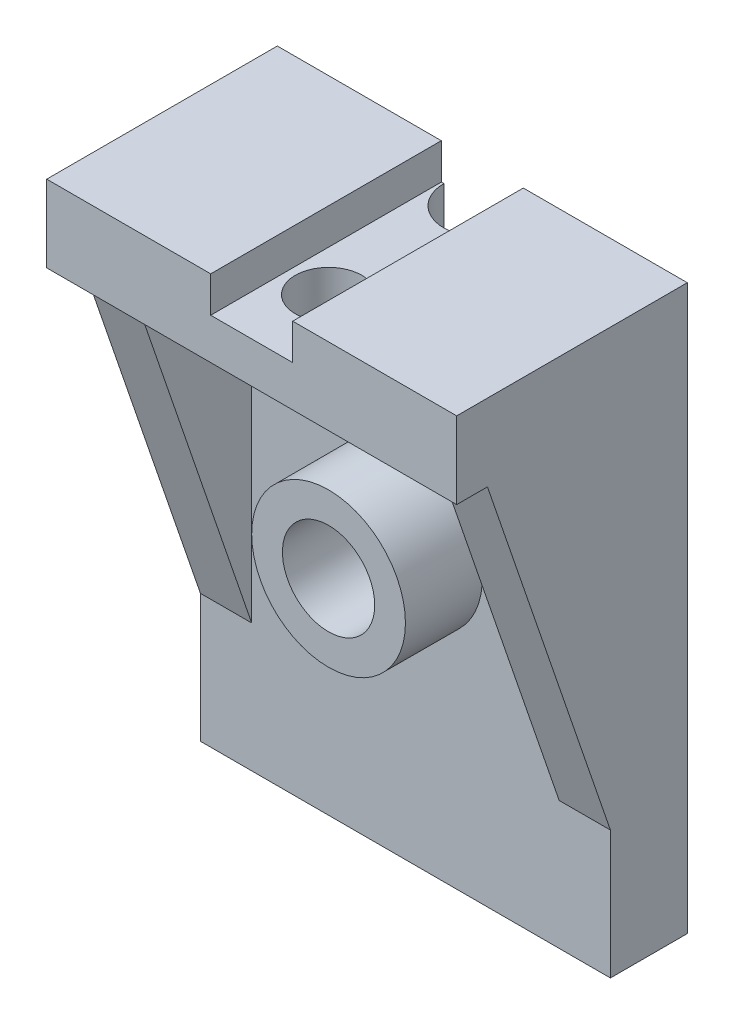
SolidWorks part; units mm, degrees
ref_plane "Спереди" through (0, 0, 0) normal (0, 0, 1) x (1, 0, 0)
ref_plane "Сверху" through (0, 0, 0) normal (0, 1, 0) x (1, 0, 0)
ref_plane "Справа" through (0, 0, 0) normal (1, 0, 0) x (0, 0, -1)
sketch "Эскиз1" plane through (0, 0, 0) normal (0, 0, 1) x (1, 0, 0)
  line L1 (-40, -55) -> (40, -55)
  line L2 (-40, -55) -> (-40, 55)
  line L3 (-40, 55) -> (40, 55)
  line L4 (40, -55) -> (40, 55)
  line L5 (-40, -55) -> (40, 55) construction
  line L6 (-40, 55) -> (40, -55) construction
  point P0 (0, 0)
  dimension "D1" = 80
  dimension "D2" = 110
extrude "Бобышка-Вытянуть1" add sketch "Эскиз1" along normal blind 15
sketch "Эскиз2" plane through (0, 0, 15) normal (0, 0, 1) x (1, 0, 0)
  line L0 (-40, 55) -> (-40, -55) construction
  line L1 (40, 55) -> (-40, 55)
  line L2 (40, 55) -> (40, 40)
  line L3 (40, 40) -> (-40, 40)
  line L4 (-40, 55) -> (-40, 40)
  dimension "D1" = 15
extrude "Бобышка-Вытянуть2" add sketch "Эскиз2" along normal blind 30
sketch "Эскиз3" plane through (40, 0, 0) normal (1, 0, 0) x (0, 0, -1)
  line L0 (-39, 40) -> (-15, -30)
  line L1 (-45, 40) -> (-15, 40) construction
  line L2 (-15, -30) -> (-15, 40)
  line L3 (-15, -55) -> (-15, 40) construction
  line L4 (-15, 40) -> (-39, 40)
  line L5 (-45, 40) -> (-45, 55) construction
  line L6 (-15, -55) -> (0, -55) construction
  dimension "D1" = 6
  dimension "D2" = 25
extrude "Бобышка-Вытянуть3" add sketch "Эскиз3" against normal blind 10
mirror "Зеркальное отражение1" about plane through (0, 0, 0) normal (1, 0, 0) of "Бобышка-Вытянуть3"
sketch "Эскиз4" plane through (0, 0, 15) normal (0, 0, 1) x (1, 0, 0)
  circle A0 centre (0, 0) radius 15
  dimension "D1" = 30
extrude "Бобышка-Вытянуть4" add sketch "Эскиз4" along normal blind 15
sketch "Эскиз5" plane through (0, 0, 30) normal (0, 0, 1) x (1, 0, 0)
  circle A2 centre (0, 0) radius 9
  circle A3 centre (0, 0) radius 9
  dimension "D1" = 6
extrude "Вырез-Вытянуть1" cut sketch "Эскиз5" against normal through all
sketch "Эскиз6" plane through (0, 40, 0) normal (0, -1, 0) x (1, 0, 0)
  line L0 (0, 15) -> (0, 45) construction
  line L1 (-30, 15) -> (30, 15) construction
  line L2 (-40, 45) -> (40, 45) construction
  circle A0 centre (0, 30) radius 6.5
  dimension "D1" = 13
extrude "Вырез-Вытянуть2" cut sketch "Эскиз6" against normal through all
sketch "Эскиз7" plane through (0, -55, 0) normal (0, -1, 0) x (1, 0, 0)
  circle A0 centre (0, 0) radius 7.5
  dimension "D1" = 15
extrude "Вырез-Вытянуть3" cut sketch "Эскиз7" against normal through all
sketch "Эскиз8" plane through (0, 0, 45) normal (0, 0, 1) x (1, 0, 0)
  line L0 (0, 55) -> (0, 40) construction
  line L1 (40, 55) -> (-40, 55) construction
  line L2 (-40, 40) -> (40, 40) construction
  line L4 (-8, 48) -> (8, 48)
  line L5 (-8, 48) -> (-8, 55)
  line L6 (-8, 55) -> (8, 55)
  line L7 (8, 48) -> (8, 55)
  line L8 (-8, 48) -> (8, 55) construction
  line L9 (-8, 55) -> (8, 48) construction
  point P6 (0, 51.5)
  dimension "D1" = 16
  dimension "D2" = 7
extrude "Вырез-Вытянуть4" cut sketch "Эскиз8" against normal through all
